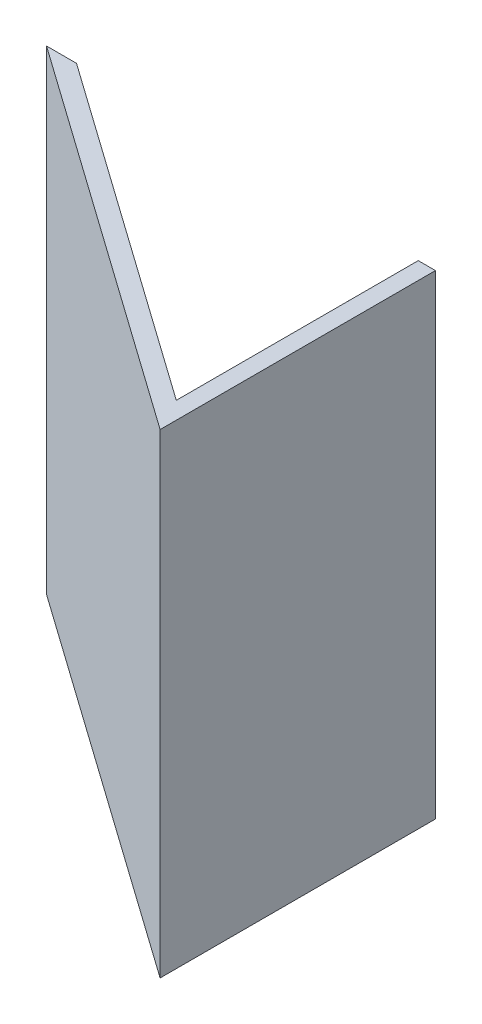
SolidWorks part; units mm, degrees
ref_plane "Front Plane" through (0, 0, 0) normal (0, 0, 1) x (1, 0, 0)
ref_plane "Top Plane" through (0, 0, 0) normal (0, 1, 0) x (1, 0, 0)
ref_plane "Right Plane" through (0, 0, 0) normal (1, 0, 0) x (0, 0, -1)
sketch "Sketch1" plane through (0, 0, 0) normal (0, 1, 0) x (1, 0, 0)
  line L1 (65.0271, 34.1908) -> (65.0271, -16.6092)
  line L2 (-6.7279, 34.1908) -> (65.0271, -16.6092)
  line L3 (-6.7279, 34.1908) -> (-1.2008, 34.1908)
  line L4 (65.0271, 34.1908) -> (61.8521, 34.1908)
  line L5 (61.8521, 34.1908) -> (61.8521, -10.4497)
  line L15 (-1.2008, 34.1908) -> (61.8521, -10.4497)
extrude "Boss-Extrude1" add sketch "Sketch1" along normal blind 87.63
